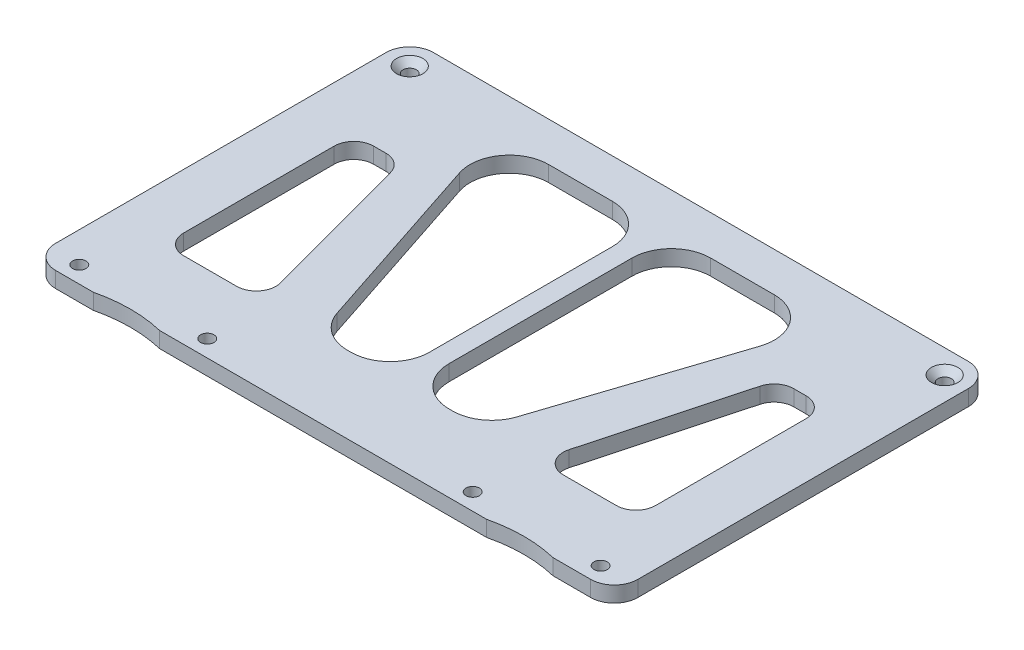
SolidWorks part; units mm, degrees
ref_plane "Front Plane" through (0, 0, 0) normal (0, 0, 1) x (1, 0, 0)
ref_plane "Top Plane" through (0, 0, 0) normal (0, 1, 0) x (1, 0, 0)
ref_plane "Right Plane" through (0, 0, 0) normal (1, 0, 0) x (0, 0, -1)
sketch "Sketch1" plane through (0, 0, 0) normal (0, 1, 0) x (1, 0, 0)
  circle A0 centre (-50, 0) radius 42.5 construction
  circle A1 centre (50, 0) radius 42.5 construction
  circle A2 centre (50, 0) radius 49 construction
  circle A3 centre (-50, 0) radius 49 construction
  circle A5 centre (-50, 0) radius 35.5 construction
  dimension "D2" = 98
  dimension "D3" = 85
  dimension "D4" = 50
  dimension "D1" = 71
  dimension "D5" = 50
sketch "Sketch2" plane through (0, 0, 0) normal (0, 1, 0) x (1, 0, 0)
  line L0 (74, 35) -> (74, 131)
  line L5 (74, 131) -> (-74, 131)
  line L6 (-74, 131) -> (-74, 35)
  line L12 (74, 35) -> (58.4261, 35)
  line L14 (41.5739, 35) -> (-41.5739, 35)
  line L16 (-58.4261, 35) -> (-74, 35)
  arc A2 (-41.5739, 35) -> (-58.4261, 35) centre (-50, 0) ccw
  arc A4 (58.4261, 35) -> (41.5739, 35) centre (50, 0) ccw
  point P0 (0, 0)
  point P1 (0, 35)
  point P2 (0, 131)
  dimension "D1" = 36
  dimension "D3" = 148
  dimension "D4" = 35
  dimension "D5" = 35
  dimension "D6" = 131
extrude "Boss-Extrude1" add sketch "Sketch2" along normal blind 4
sketch "Sketch3" plane through (0, 4, 0) normal (0, 1, 0) x (1, 0, 0)
  line L0 (-50, 0) -> (-50, -42.5) construction
  line L1 (0, -2.2) -> (0, 2.2) construction
  circle A0 centre (-50, 0) radius 42.5 construction
  circle A1 centre (-66.264, -39.2649) radius 1.7
  circle A4 centre (-50, -42.5) radius 1 construction
  circle A5 centre (-66.264, 39.2649) radius 1.7
  circle A6 centre (-33.736, 39.2649) radius 1.7
  circle A7 centre (-10.7351, 16.264) radius 1.7
  circle A8 centre (-10.7351, -16.264) radius 1.7
  circle A9 centre (-33.736, -39.2649) radius 1.7
  circle A10 centre (10.7351, 16.264) radius 1.7
  circle A11 centre (33.736, 39.2649) radius 1.7
  circle A12 centre (66.264, 39.2649) radius 1.7
  circle A14 centre (10.7351, -16.264) radius 1.7
  circle A15 centre (33.736, -39.2649) radius 1.7
  circle A16 centre (66.264, -39.2649) radius 1.7
  circle A18 centre (-89.2649, -16.264) radius 1.7 [skipped]
  circle A19 centre (-89.2649, 16.264) radius 1.7 [skipped]
  point P26 (-50, 0)
  dimension "D1" = 3.4
  dimension "D2" = 2
  dimension "D6" = 45
  dimension "D3" = 22.5
  dimension "D5" = 45
  dimension "D4" = 8
extrude "Cut-Extrude1" cut sketch "Sketch3" against normal up to surface (4 mm away)
fillet "Fillet1" radius 6 4 edges at (-74, 2, -35) (-74, 2, -131) (74, 2, -131) (74, 2, -35)
sketch "Sketch4" plane through (0, 4, 0) normal (0, 1, 0) x (1, 0, 0)
  circle A0 centre (68, 125) radius 1.7
  circle A1 centre (-68, 125) radius 1.7
  dimension "D1" = 3.4
extrude "Cut-Extrude2" cut sketch "Sketch4" against normal blind 10
sketch "Sketch5" plane through (0, 4, 0) normal (0, 1, 0) x (1, 0, 0)
  line L0 (-12.5, 121) -> (-28.6748, 121)
  line L1 (-38.1722, 107.8696) -> (-22.8516, 61.3878)
  line L2 (0, 35) -> (0, 131) construction
  line L3 (-41.5739, 35) -> (41.5739, 35) construction
  line L4 (68, 131) -> (-68, 131) construction
  line L5 (-13.3542, 54.5181) -> (-12.5, 54.5181)
  line L6 (-2.5, 64.5181) -> (-2.5, 111)
  line L7 (-60, 59.5181) -> (-60, 97.7986)
  line L8 (-55, 54.5181) -> (-41.5244, 54.5181)
  line L9 (-36.6963, 60.8181) -> (-47.0037, 99.0986)
  line L10 (-51.8318, 102.7986) -> (-55, 102.7986)
  arc A0 (-12.5, 121) -> (-2.5, 111) centre (-12.5, 111) cw
  arc A1 (-28.6748, 121) -> (-38.1722, 107.8696) centre (-28.6748, 111) ccw
  arc A2 (-22.8516, 61.3878) -> (-13.3542, 54.5181) centre (-13.3542, 64.5181) ccw
  arc A3 (-12.5, 54.5181) -> (-2.5, 64.5181) centre (-12.5, 64.5181) ccw
  arc A4 (-47.0037, 99.0986) -> (-51.8318, 102.7986) centre (-51.8318, 97.7986) ccw
  arc A5 (-55, 102.7986) -> (-60, 97.7986) centre (-55, 97.7986) ccw
  arc A6 (-60, 59.5181) -> (-55, 54.5181) centre (-55, 59.5181) ccw
  arc A7 (-41.5244, 54.5181) -> (-36.6963, 60.8181) centre (-41.5244, 59.5181) ccw
  point P2 (-20.5874, 121)
  point P13 (-2.5, 121)
  point P16 (-42.5, 121)
  point P19 (-20.5874, 54.5181)
  point P29 (-48, 102.7986)
  point P32 (-60, 102.7986)
  point P35 (-60, 54.5181)
  point P38 (-35, 54.5181)
  dimension "D5" = 10
  dimension "D10" = 5
  dimension "D1" = 40
  dimension "D2" = 70
  dimension "D3" = 5
  dimension "D4" = 10
  dimension "D6" = 25
  dimension "D7" = 12
  dimension "D8" = 50
  dimension "D9" = 60
extrude "Cut-Extrude3" cut sketch "Sketch5" against normal blind 10
mirror "Mirror1" about plane through (0, 0, 0) normal (1, 0, 0) of "Cut-Extrude3"
chamfer "Chamfer1" distance 1.65 angle 45 2 edges at (-68, 4, -123.3) (68, 4, -123.3)
